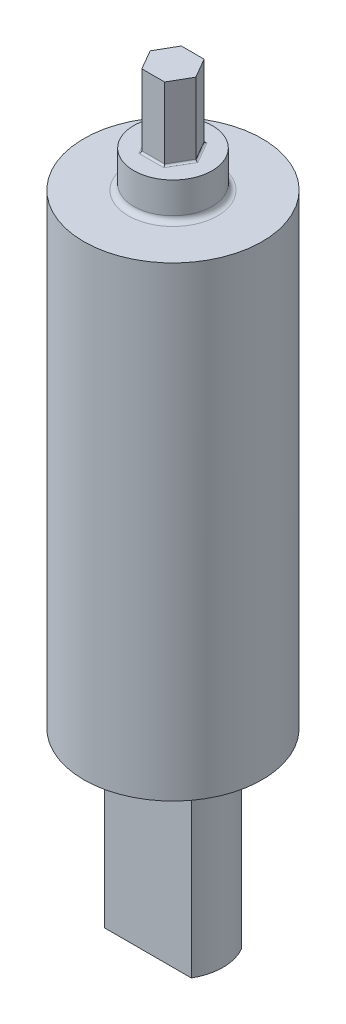
SolidWorks part; units mm, degrees
ref_plane "Plano frontal" through (0, 0, 0) normal (0, 0, 1) x (1, 0, 0)
ref_plane "Plano superior" through (0, 0, 0) normal (0, 1, 0) x (1, 0, 0)
ref_plane "Plano direito" through (0, 0, 0) normal (1, 0, 0) x (0, 0, -1)
sketch "Croquis5" plane through (0, 0, 0) normal (0, 1, 0) x (1, 0, 0)
  circle A0 centre (0, 0) radius 4.9
  dimension "D1" = 9.8
extrude "Saliente-Extruir1" add sketch "Croquis5" against normal blind 35.6
sketch "Croquis6" plane through (0, 0, 0) normal (0, 1, 0) x (1, 0, 0)
  circle A0 centre (0, 0) radius 2.15
  dimension "D1" = 4.3
extrude "Saliente-Extruir2" add sketch "Croquis6" along normal blind 2
sketch "Croquis7" plane through (0, 2, 0) normal (0, 1, 0) x (1, 0, 0)
  line L1 (1.2529, 0) -> (0.6264, 1.085)
  line L2 (0.6264, 1.085) -> (-0.6264, 1.085)
  line L3 (-0.6264, 1.085) -> (-1.2529, 0)
  line L4 (-1.2529, 0) -> (-0.6264, -1.085)
  line L5 (-0.6264, -1.085) -> (0.6264, -1.085)
  line L6 (0.6264, -1.085) -> (1.2529, 0)
  circle A0 centre (0, 0) radius 1.085 construction
  dimension "D1" = 2.17
extrude "Saliente-Extruir3" add sketch "Croquis7" along normal blind 4
fillet "Redondeo3" radius 0.1 6 edges at (-0.9396, 2, -0.5425) (0, 2, -1.085) (0.9396, 2, -0.5425) (0.9396, 2, 0.5425) (0, 2, 1.085) (-0.9396, 2, 0.5425)
fillet "Redondeo4" radius 0.3 1 edges at (0, 0, 2.15)
sketch "Croquis8" plane through (0, -35.6, 0) normal (0, -1, 0) x (1, 0, 0)
  line L9 (-2.3816, 1.375) -> (2.3816, 1.375)
  line L10 (-2.3816, -1.375) -> (2.3816, -1.375)
  arc A0 (2.3816, -1.375) -> (2.3816, 1.375) centre (0, 0) ccw
  arc A1 (-2.3816, 1.375) -> (-2.3816, -1.375) centre (0, 0) ccw
  circle A2 centre (0, 0) radius 4.9
  point P12 (0, 0.6875)
  point P15 (0, 1.375)
  point P17 (0, -1.375)
  circle M10 centre (0, 0) radius 4.9
  dimension "D1" = 5.5
  dimension "D2" = 1.375
  dimension "D3" = 1.375
extrude "Cortar-Extruir1" cut sketch "Croquis8" against normal blind 10 contours A1 L9 A0 L10 M10
fillet "Redondeo5" radius 0.3 4 edges at (-2.75, -25.6, 0) (0, -25.6, -1.375) (2.75, -25.6, 0) (0, -25.6, 1.375)
